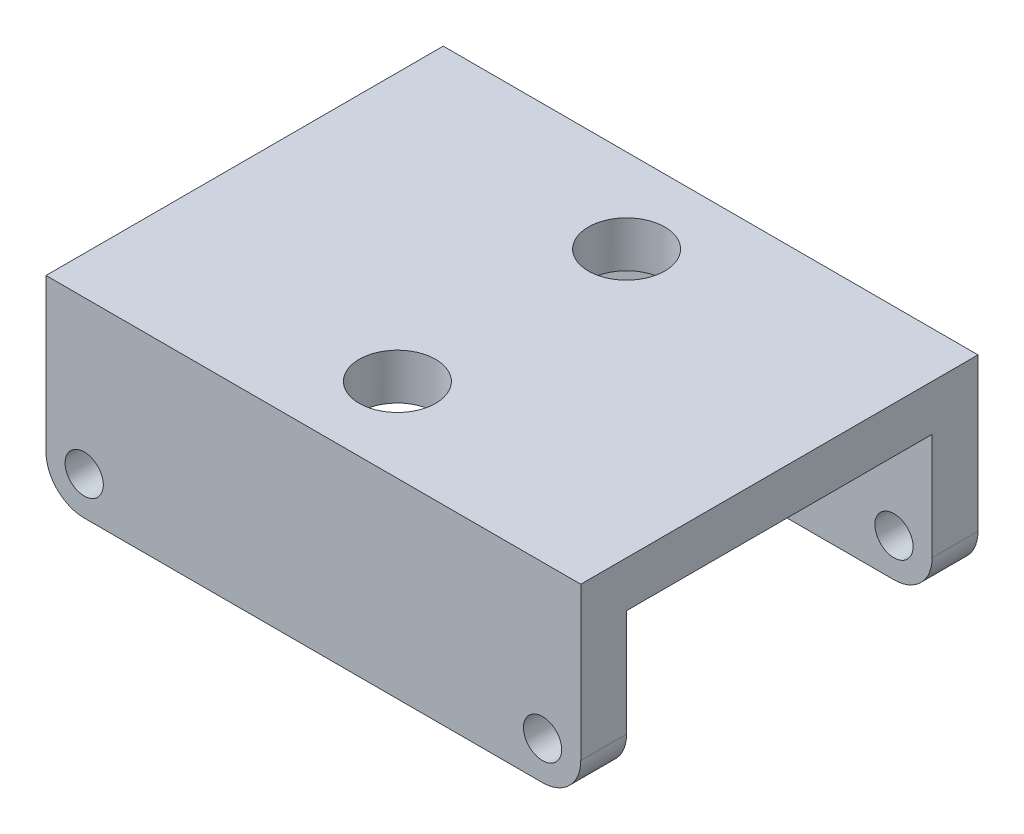
SolidWorks part; units mm, degrees
ref_plane "前视基准面" through (0, 0, 0) normal (0, 0, 1) x (1, 0, 0)
ref_plane "上视基准面" through (0, 0, 0) normal (0, 1, 0) x (1, 0, 0)
ref_plane "右视基准面" through (0, 0, 0) normal (1, 0, 0) x (0, 0, -1)
sketch "草图1" plane through (0, 0, 0) normal (0, 0, 1) x (1, 0, 0)
  line L0 (-47.7702, 10.4554) -> (-47.7702, -14.5446)
  line L1 (-47.7702, -14.5446) -> (22.2298, -14.5446)
  line L2 (22.2298, -14.5446) -> (22.2298, 10.4554)
  line L3 (22.2298, 10.4554) -> (-47.7702, 10.4554)
  line L4 (-12.7702, 10.4554) -> (-12.7702, -67.6473) construction
  circle A0 centre (-42.7702, -9.5446) radius 2.5
  circle A2 centre (17.2298, -9.5446) radius 2.5
  dimension "D3" = 5
  dimension "D1" = 70
  dimension "D2" = 25
  dimension "D4" = 5
  dimension "D5" = 5
extrude "凸台-拉伸1" add sketch "草图1" along normal blind 52
sketch "草图2" plane through (-47.7702, 0, 0) normal (-1, 0, 0) x (0, 0, 1)
  line L0 (6, 4.4554) -> (6, -14.5446)
  line L1 (52, -14.5446) -> (0, -14.5446) construction
  line L2 (6, -14.5446) -> (46, -14.5446)
  line L3 (46, -14.5446) -> (46, 4.4554)
  line L4 (46, 4.4554) -> (6, 4.4554)
  line L5 (0, 10.4554) -> (0, -14.5446) construction
  line L6 (52, 10.4554) -> (0, 10.4554) construction
  line L7 (52, 10.4554) -> (52, -14.5446) construction
  dimension "D1" = 6
  dimension "D2" = 6
  dimension "D3" = 6
fillet "圆角6" radius 5 1 edges at (-47.7702, -14.5446, 26)
fillet "圆角7" radius 5 1 edges at (22.2298, -14.5446, 26)
extrude "切除-拉伸2" cut sketch "草图2" against normal through all
sketch "草图3" plane through (0, 10.4554, 0) normal (0, 1, 0) x (1, 0, 0)
  line L0 (-47.7702, -26) -> (46.922, -26) construction
  line L1 (-47.7702, -52) -> (-47.7702, 0) construction
  line L2 (22.2298, 0) -> (-47.7702, 0) construction
  line L3 (22.2298, -52) -> (22.2298, 0) construction
  circle A0 centre (-12.7702, -11) radius 5
  circle A2 centre (-12.7702, -41) radius 5
  dimension "D1" = 10
  dimension "D2" = 11
  dimension "D3" = 35
extrude "切除-拉伸3" cut sketch "草图3" against normal through all contours A0 | A2
